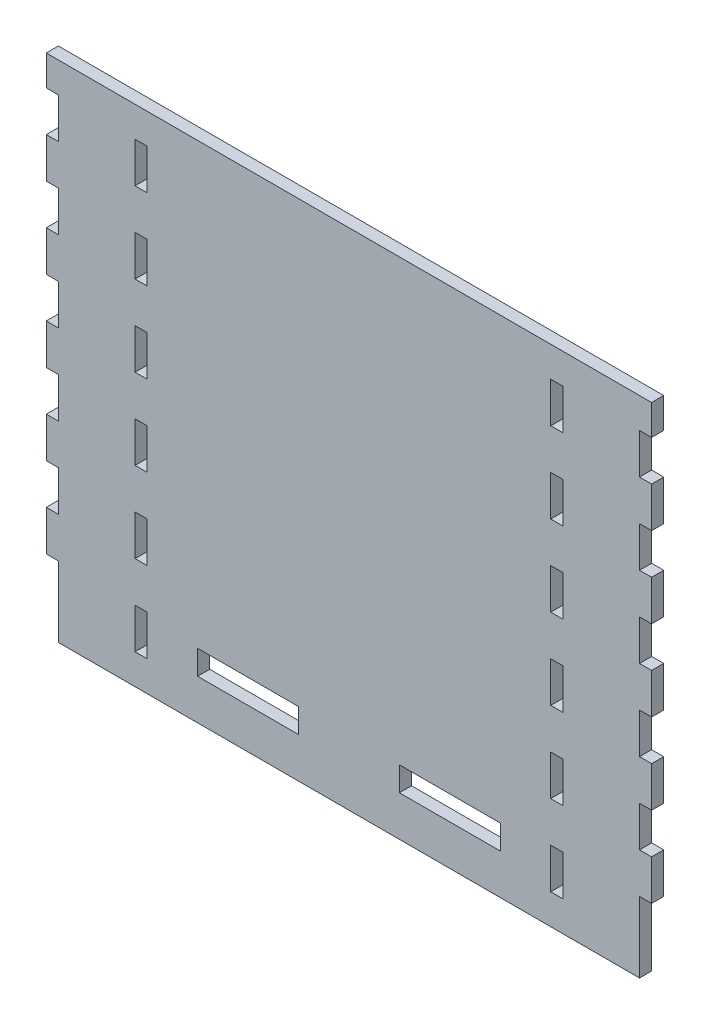
SolidWorks part; units mm, degrees
ref_plane "前视基准面" through (0, 0, 0) normal (0, 0, 1) x (1, 0, 0)
ref_plane "上视基准面" through (0, 0, 0) normal (0, 1, 0) x (1, 0, 0)
ref_plane "右视基准面" through (0, 0, 0) normal (1, 0, 0) x (0, 0, -1)
sketch "草图1" plane through (0, 0, 0) normal (0, 0, 1) x (1, 0, 0)
  line L0 (-99.9501, 5.4126) -> (-99.9501, -14.5874)
  line L1 (-93.9501, 120.4126) -> (194.0499, 120.4126)
  line L2 (-99.9501, 5.4126) -> (-93.9501, 5.4126)
  line L3 (-93.9501, 5.4126) -> (-93.9501, 25.4126)
  line L4 (-93.9501, 25.4126) -> (-99.9501, 25.4126)
  line L5 (-99.9501, 25.4126) -> (-99.9501, 45.4126)
  line L6 (-99.9501, 45.4126) -> (-93.9501, 45.4126)
  line L7 (-93.9501, 45.4126) -> (-93.9501, 65.4126)
  line L8 (-93.9501, 65.4126) -> (-99.9501, 65.4126)
  line L9 (-99.9501, 65.4126) -> (-99.9501, 85.4126)
  line L10 (-99.9501, 85.4126) -> (-93.9501, 85.4126)
  line L11 (-93.9501, 85.4126) -> (-93.9501, 105.4126)
  line L12 (-93.9501, 105.4126) -> (-99.9501, 105.4126)
  line L13 (-99.9501, 105.4126) -> (-99.9501, 120.4126)
  line L14 (-99.9501, -94.5874) -> (-93.9501, -94.5874)
  line L15 (-99.9501, -74.5874) -> (-99.9501, -94.5874)
  line L16 (-93.9501, -74.5874) -> (-99.9501, -74.5874)
  line L17 (-93.9501, -54.5874) -> (-93.9501, -74.5874)
  line L18 (-99.9501, -54.5874) -> (-93.9501, -54.5874)
  line L19 (-99.9501, -34.5874) -> (-99.9501, -54.5874)
  line L20 (-93.9501, -34.5874) -> (-99.9501, -34.5874)
  line L21 (-93.9501, -14.5874) -> (-93.9501, -34.5874)
  line L22 (-99.9501, -14.5874) -> (-93.9501, -14.5874)
  line L23 (-93.9501, -129.5874) -> (194.0499, -129.5874)
  line L24 (200.0499, -14.5874) -> (194.0499, -14.5874)
  line L25 (194.0499, -14.5874) -> (194.0499, -34.5874)
  line L26 (194.0499, -34.5874) -> (200.0499, -34.5874)
  line L27 (200.0499, -34.5874) -> (200.0499, -54.5874)
  line L28 (200.0499, -54.5874) -> (194.0499, -54.5874)
  line L29 (194.0499, -54.5874) -> (194.0499, -74.5874)
  line L30 (194.0499, -74.5874) -> (200.0499, -74.5874)
  line L31 (200.0499, -74.5874) -> (200.0499, -94.5874)
  line L32 (200.0499, -94.5874) -> (194.0499, -94.5874)
  line L33 (200.0499, 105.4126) -> (200.0499, 120.4126)
  line L34 (194.0499, 105.4126) -> (200.0499, 105.4126)
  line L35 (194.0499, 85.4126) -> (194.0499, 105.4126)
  line L36 (200.0499, 85.4126) -> (194.0499, 85.4126)
  line L37 (200.0499, 65.4126) -> (200.0499, 85.4126)
  line L38 (194.0499, 65.4126) -> (200.0499, 65.4126)
  line L39 (194.0499, 45.4126) -> (194.0499, 65.4126)
  line L40 (200.0499, 45.4126) -> (194.0499, 45.4126)
  line L41 (200.0499, 25.4126) -> (200.0499, 45.4126)
  line L42 (194.0499, 25.4126) -> (200.0499, 25.4126)
  line L43 (194.0499, 5.4126) -> (194.0499, 25.4126)
  line L44 (200.0499, 5.4126) -> (194.0499, 5.4126)
  line L45 (200.0499, -14.5874) -> (200.0499, 5.4126)
  line L48 (-93.9501, -94.5874) -> (-93.9501, -129.5874)
  line L49 (194.0499, -129.5874) -> (194.0499, -94.5874)
  line L50 (-99.9501, 120.4126) -> (-93.9501, 120.4126)
  line L51 (75.0499, -109.5874) -> (75.0499, -97.5874)
  line L52 (200.0499, 120.4126) -> (194.0499, 120.4126)
  line L53 (75.0499, -97.5874) -> (125.0499, -97.5874)
  line L54 (125.0499, -97.5874) -> (125.0499, -109.5874)
  line L55 (125.0499, -109.5874) -> (75.0499, -109.5874)
  line L56 (156.0499, 25.4126) -> (156.0499, 5.4126)
  line L57 (156.0499, 5.4126) -> (150.0499, 5.4126)
  line L58 (150.0499, 5.4126) -> (150.0499, 25.4126)
  line L59 (150.0499, 25.4126) -> (156.0499, 25.4126)
  line L60 (156.0499, -74.5874) -> (156.0499, -54.5874)
  line L61 (156.0499, 45.4126) -> (150.0499, 45.4126)
  line L62 (150.0499, 45.4126) -> (150.0499, 65.4126)
  line L63 (150.0499, 65.4126) -> (156.0499, 65.4126)
  line L64 (156.0499, -114.5874) -> (156.0499, -94.5874)
  line L65 (156.0499, 85.4126) -> (150.0499, 85.4126)
  line L66 (150.0499, 85.4126) -> (150.0499, 105.4126)
  line L67 (150.0499, 105.4126) -> (156.0499, 105.4126)
  line L68 (156.0499, 105.4126) -> (156.0499, 85.4126)
  line L69 (156.0499, 65.4126) -> (156.0499, 45.4126)
  line L70 (150.0499, -114.5874) -> (156.0499, -114.5874)
  line L71 (150.0499, -94.5874) -> (150.0499, -114.5874)
  line L72 (156.0499, -94.5874) -> (150.0499, -94.5874)
  line L73 (150.0499, -74.5874) -> (156.0499, -74.5874)
  line L74 (150.0499, -54.5874) -> (150.0499, -74.5874)
  line L75 (156.0499, -54.5874) -> (150.0499, -54.5874)
  line L76 (150.0499, -34.5874) -> (156.0499, -34.5874)
  line L77 (150.0499, -14.5874) -> (150.0499, -34.5874)
  line L78 (156.0499, -14.5874) -> (150.0499, -14.5874)
  line L79 (156.0499, -34.5874) -> (156.0499, -14.5874)
  line L80 (-55.9501, -34.5874) -> (-55.9501, -14.5874)
  line L81 (-55.9501, -14.5874) -> (-49.9501, -14.5874)
  line L82 (-49.9501, -14.5874) -> (-49.9501, -34.5874)
  line L83 (-49.9501, -34.5874) -> (-55.9501, -34.5874)
  line L84 (-55.9501, -54.5874) -> (-49.9501, -54.5874)
  line L85 (-49.9501, -54.5874) -> (-49.9501, -74.5874)
  line L86 (-49.9501, -74.5874) -> (-55.9501, -74.5874)
  line L87 (-55.9501, -94.5874) -> (-49.9501, -94.5874)
  line L88 (-49.9501, -94.5874) -> (-49.9501, -114.5874)
  line L89 (-49.9501, -114.5874) -> (-55.9501, -114.5874)
  line L90 (-55.9501, 65.4126) -> (-55.9501, 45.4126)
  line L91 (-55.9501, 105.4126) -> (-55.9501, 85.4126)
  line L92 (-49.9501, 105.4126) -> (-55.9501, 105.4126)
  line L93 (-49.9501, 85.4126) -> (-49.9501, 105.4126)
  line L94 (-55.9501, 85.4126) -> (-49.9501, 85.4126)
  line L95 (-55.9501, -114.5874) -> (-55.9501, -94.5874)
  line L96 (-49.9501, 65.4126) -> (-55.9501, 65.4126)
  line L97 (-49.9501, 45.4126) -> (-49.9501, 65.4126)
  line L98 (-55.9501, 45.4126) -> (-49.9501, 45.4126)
  line L99 (-55.9501, -74.5874) -> (-55.9501, -54.5874)
  line L100 (-49.9501, 25.4126) -> (-55.9501, 25.4126)
  line L101 (-49.9501, 5.4126) -> (-49.9501, 25.4126)
  line L102 (-55.9501, 5.4126) -> (-49.9501, 5.4126)
  line L103 (-55.9501, 25.4126) -> (-55.9501, 5.4126)
  line L105 (25.0499, -109.5874) -> (25.0499, -97.5874)
  line L106 (25.0499, -97.5874) -> (-24.9501, -97.5874)
  line L107 (-24.9501, -97.5874) -> (-24.9501, -109.5874)
  line L108 (-24.9501, -109.5874) -> (25.0499, -109.5874)
extrude "凸台-拉伸1" add sketch "草图1" along normal blind 6
